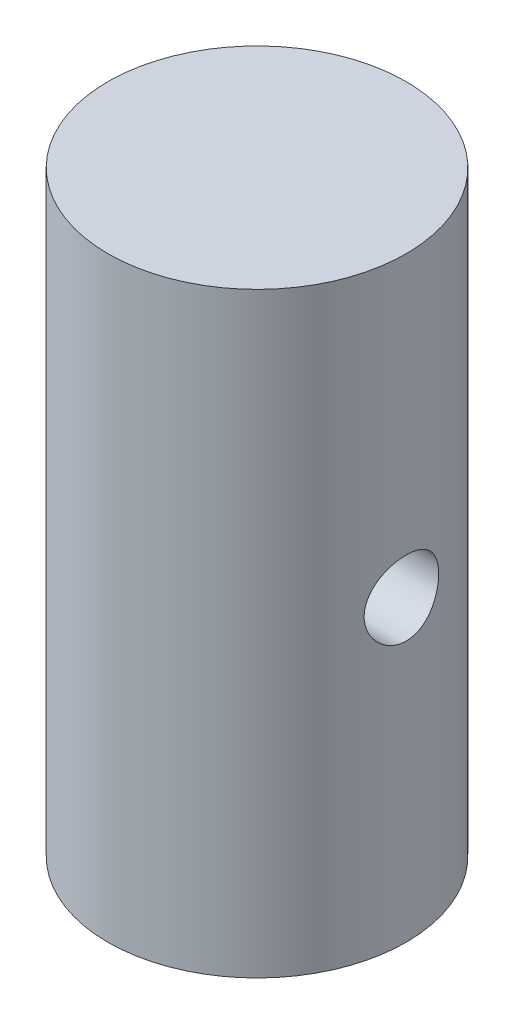
SolidWorks part; units mm, degrees
ref_plane "前视基准面" through (0, 0, 0) normal (0, 0, 1) x (1, 0, 0)
ref_plane "上视基准面" through (0, 0, 0) normal (0, 1, 0) x (1, 0, 0)
ref_plane "右视基准面" through (0, 0, 0) normal (1, 0, 0) x (0, 0, -1)
other "Configuration Table"
sketch "草图1" plane through (0, 0, 0) normal (0, 1, 0) x (1, 0, 0)
  circle A0 centre (0, 0) radius 10
extrude "凸台-拉伸1" add sketch "草图1" along normal blind 40
sketch "草图2" plane through (0, 0, 0) normal (1, 0, 0) x (0, 0, -1)
  line L0 (10, 40) -> (-10, 40) construction
  line L3 (-10, 40) -> (-10, 0) construction
  circle A0 centre (0, 20) radius 2.5
  point P6 (10, 24.7377)
  dimension "D1" = 20
  dimension "D2" = 10
extrude "切除-拉伸1" cut sketch "草图2" against normal mid plane 40
